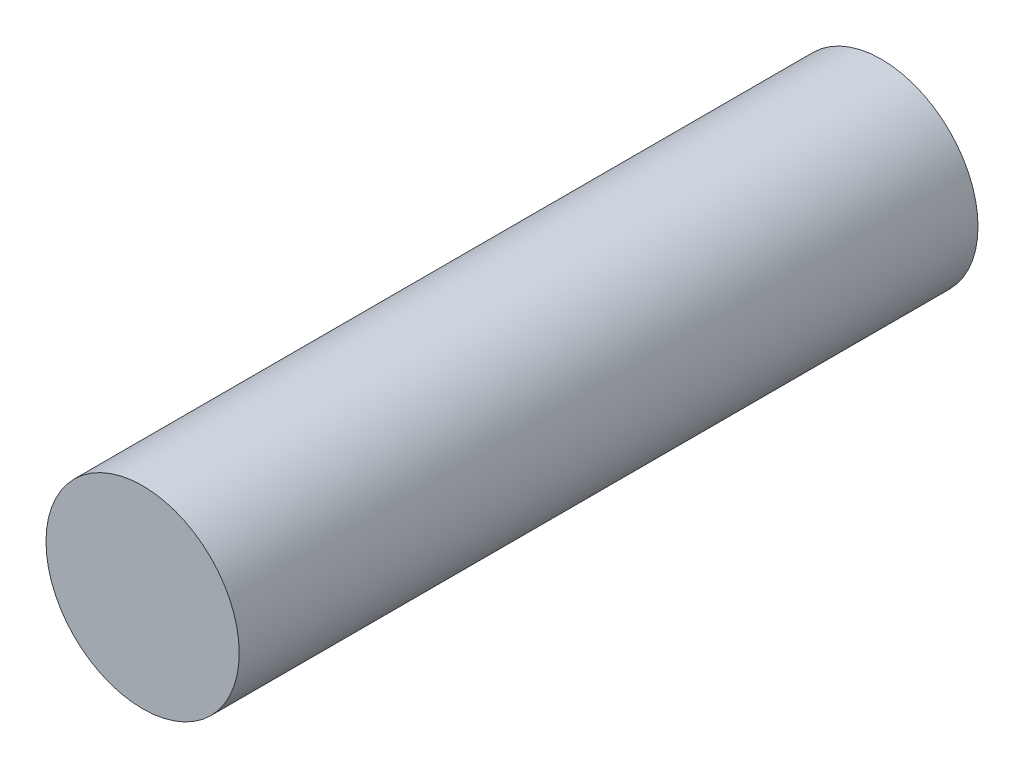
SolidWorks part; units mm, degrees
ref_plane "Front Plane" through (0, 0, 0) normal (0, 0, 1) x (1, 0, 0)
ref_plane "Top Plane" through (0, 0, 0) normal (0, 1, 0) x (1, 0, 0)
ref_plane "Right Plane" through (0, 0, 0) normal (1, 0, 0) x (0, 0, -1)
sketch "Sketch1" plane through (0, 0, 0) normal (0, 0, 1) x (1, 0, 0)
  circle A0 centre (0, 0) radius 8.5
  dimension "D1" = 17
extrude "Boss-Extrude1" add sketch "Sketch1" against normal blind 65
